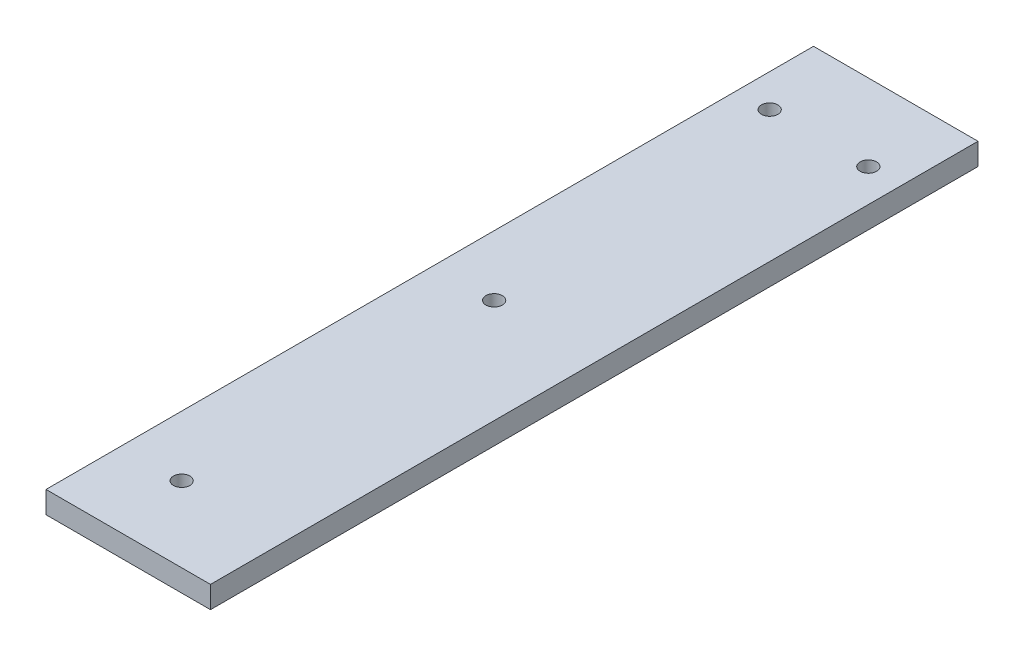
SolidWorks part; units mm, degrees
ref_plane "Front Plane" through (0, 0, 0) normal (0, 0, 1) x (1, 0, 0)
ref_plane "Top Plane" through (0, 0, 0) normal (0, 1, 0) x (1, 0, 0)
ref_plane "Right Plane" through (0, 0, 0) normal (1, 0, 0) x (0, 0, -1)
sketch "Sketch1" plane through (0, 0, 0) normal (0, 0, 1) x (1, 0, 0)
  line L1 (15, 0) -> (0, 0)
  line L2 (15, 0) -> (15, 2)
  line L3 (15, 2) -> (0, 2)
  line L4 (0, 0) -> (0, 2)
  dimension "D1" = 2
  dimension "D2" = 15
extrude "Boss-Extrude1" add sketch "Sketch1" along normal blind 70
sketch "Sketch2" plane through (0, 2, 0) normal (0, 1, 0) x (1, 0, 0)
  circle A0 centre (12, -7) radius 0.75 construction
  circle A1 centre (12, -7) radius 0.75
  circle A2 centre (3, -7) radius 0.75 construction
  circle A3 centre (3, -7) radius 0.75
  circle A4 centre (5.5, -34.6286) radius 0.75 construction
  circle A5 centre (5.5, -34.6286) radius 0.75
  circle A6 centre (5.5, -63.1286) radius 0.75 construction
  circle A7 centre (5.5, -63.1286) radius 0.75
extrude "Cut-Extrude1" cut sketch "Sketch2" against normal through all
